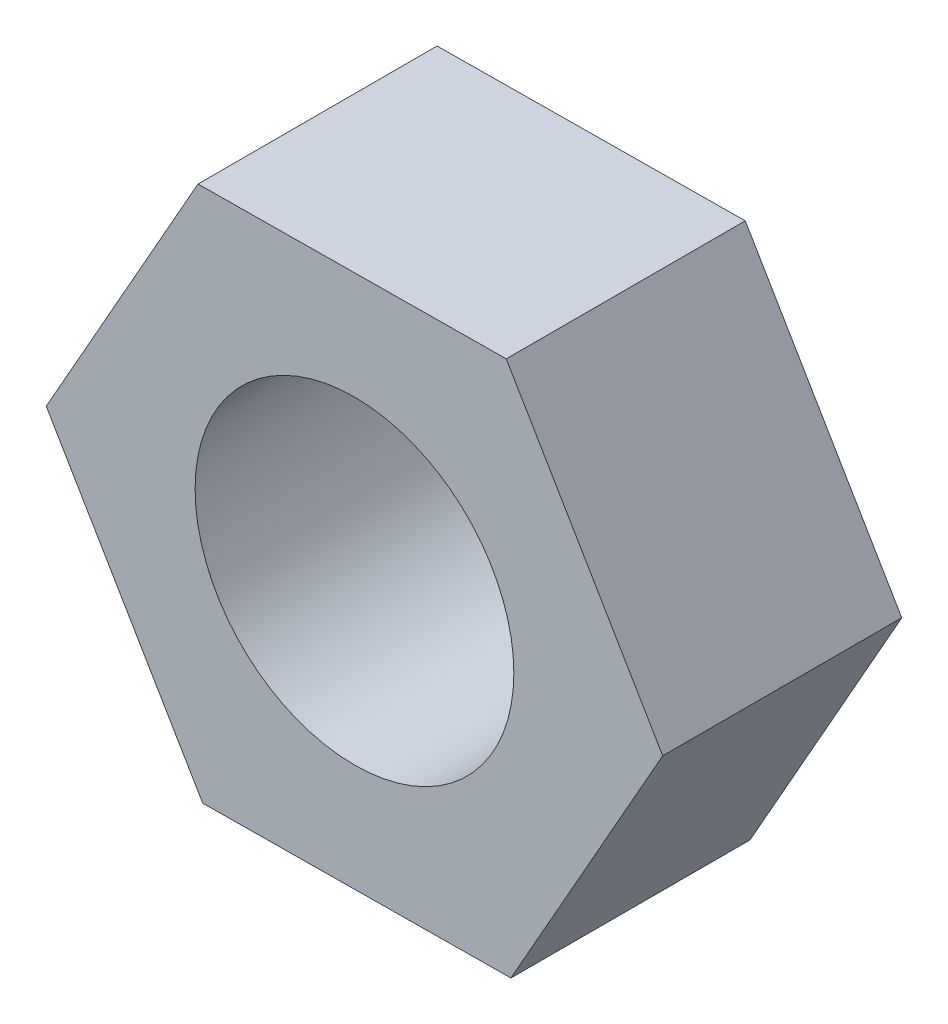
SolidWorks part; units mm, degrees
ref_plane "前视基准面" through (0, 0, 0) normal (0, 0, 1) x (1, 0, 0)
ref_plane "上视基准面" through (0, 0, 0) normal (0, 1, 0) x (1, 0, 0)
ref_plane "右视基准面" through (0, 0, 0) normal (1, 0, 0) x (0, 0, -1)
sketch "草图1" plane through (0, 0, 0) normal (0, 0, 1) x (1, 0, 0)
  line L1 (1.9635, -3.3328) -> (3.8681, 0.0341)
  line L2 (3.8681, 0.0341) -> (1.9046, 3.3669)
  line L3 (1.9046, 3.3669) -> (-1.9635, 3.3328)
  line L4 (-1.9635, 3.3328) -> (-3.8681, -0.0341)
  line L5 (-3.8681, -0.0341) -> (-1.9046, -3.3669)
  line L6 (-1.9046, -3.3669) -> (1.9635, -3.3328)
  circle A0 centre (0, 0) radius 3.35 construction
  circle A1 centre (0, 0) radius 2
  dimension "D1" = 6.7
  dimension "D2" = 4
extrude "凸台-拉伸1" add sketch "草图1" along normal blind 3
